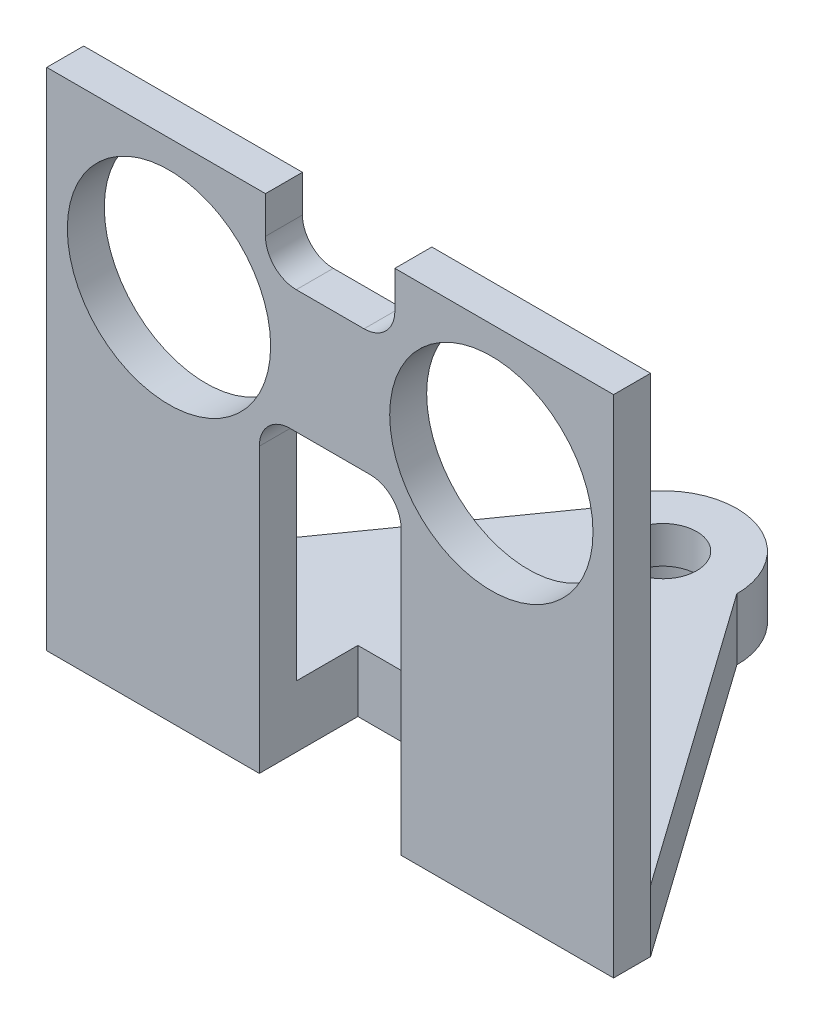
SolidWorks part; units mm, degrees
ref_plane "Front Plane" through (0, 0, 0) normal (0, 0, 1) x (1, 0, 0)
ref_plane "Top Plane" through (0, 0, 0) normal (0, 1, 0) x (1, 0, 0)
ref_plane "Right Plane" through (0, 0, 0) normal (1, 0, 0) x (0, 0, -1)
sketch "Sketch1" plane through (0, 0, 0) normal (0, 0, 1) x (1, 0, 0)
  line L0 (0, 0) -> (0, 10)
  line L1 (2.75, 10) -> (-2.75, 10)
  line L2 (-5.25, 12.5) -> (-5.25, 15.5)
  line L3 (-5.25, 15.5) -> (-23, 15.5)
  line L4 (-23, 15.5) -> (-23, -20.5)
  line L8 (-23, -20.5) -> (-5.75, -20.5)
  line L9 (-5.75, -20.5) -> (-5.75, -2.5)
  line L11 (-3.25, 0) -> (3.25, 0)
  line L12 (5.75, -20.5) -> (5.75, -2.5)
  line L13 (23, -20.5) -> (5.75, -20.5)
  line L14 (23, 15.5) -> (23, -20.5)
  line L15 (5.25, 15.5) -> (23, 15.5)
  line L16 (5.25, 12.5) -> (5.25, 15.5)
  circle A0 centre (-13.08, 5) radius 8.25
  arc A1 (-5.75, -2.5) -> (-3.25, 0) centre (-3.25, -2.5) cw
  arc A2 (-2.75, 10) -> (-5.25, 12.5) centre (-2.75, 12.5) cw
  circle A3 centre (13.08, 5) radius 8.25
  arc A4 (2.75, 10) -> (5.25, 12.5) centre (2.75, 12.5) ccw
  arc A5 (5.75, -2.5) -> (3.25, 0) centre (3.25, -2.5) ccw
  point P3 (0, 5)
  dimension "D8" = 16.5
  dimension "D10" = 2.5
  dimension "D1" = 17.75
  dimension "D2" = 36
  dimension "D3" = 10.5
  dimension "D4" = 5.5
  dimension "D5" = 5
  dimension "D6" = 17.25
  dimension "D7" = 13.08
  dimension "D9" = 5
extrude "Boss-Extrude1" add sketch "Sketch1" along normal blind 3 contours L1 A2 L2 L3 L4 L8 L9 A1 L11 L0 A0 | A5 L12 L13 L14 L15 L16 A4 L1 L0 L11 A3
sketch "Sketch2" plane through (0, -20.5, 0) normal (0, -1, 0) x (1, 0, 0)
  line L0 (-3.25, 3) -> (3.25, 3) construction
  line L1 (-23, 0) -> (-6, -24)
  line L2 (6, -24) -> (23, 0)
  line L3 (0, 0) -> (0, -5.5) construction
  line L4 (-23, 0) -> (-23, 3)
  line L5 (-23, 3) -> (-5.75, 3)
  line L6 (23, 3) -> (23, 0)
  line L7 (-5.75, 3) -> (-5.75, -5)
  line L8 (5.75, 3) -> (5.75, -5)
  line L9 (5.75, -5) -> (-5.75, -5)
  line L10 (5.75, 3) -> (23, 3)
  line L11 (-2.1, -7.6) -> (-3.5, -24)
  line L12 (2.1, -7.6) -> (3.5, -24)
  line L13 (0, -20.5) -> (0, -30) construction
  arc A0 (-6, -24) -> (6, -24) centre (0, -24) ccw
  arc A2 (-3.4494, -23.4068) -> (3.4494, -23.4068) centre (0, -24) ccw
  arc A3 (2.1, -7.6) -> (-2.1, -7.6) centre (0, -7.6) ccw
  point P0 (0, -30)
  point P5 (0, -7.6)
  point P26 (0, -24)
  line M12 (5.75, 0) -> (23, 0)
  line M13 (23, 0) -> (23, 3)
  line M14 (23, 3) -> (5.75, 3)
  line M15 (5.75, 3) -> (5.75, 0)
  dimension "D2" = 6
  dimension "D6" = 7
  dimension "D7" = 2.1
  dimension "D3" = 27
  dimension "D4" = 5
  dimension "D5" = 16.4
extrude "Boss-Extrude2" add sketch "Sketch2" along normal blind 5 contours L1 A0 L2 L8 L9 L7 L5 L4 A3 L12 A2 L11 M12 | M15 M12 M13 M14
sketch "Sketch3" plane through (0, -20.5, 0) normal (0, 1, 0) x (1, 0, 0)
  line L0 (2.1, 7.6) -> (3.4494, 23.4068) construction
  line L1 (-2.1, 7.6) -> (-3.4494, 23.4068) construction
  line L2 (2.1, 7.6) -> (3.4494, 23.4068)
  line L3 (-2.1, 7.6) -> (-3.4494, 23.4068)
  arc A0 (-2.1, 7.6) -> (2.1, 7.6) centre (0, 7.6) ccw construction
  arc A1 (3.4494, 23.4068) -> (-3.4494, 23.4068) centre (0, 24) ccw construction
  arc A2 (-2.1, 7.6) -> (2.1, 7.6) centre (0, 7.6) ccw
  arc A3 (3.4494, 23.4068) -> (-3.4494, 23.4068) centre (0, 24) ccw
extrude "Boss-Extrude3" add sketch "Sketch3" against normal blind 3
sketch "Sketch4" plane through (0, -23.5, 0) normal (0, -1, 0) x (1, 0, 0)
  line L1 (5.75, -5) -> (-5.75, -5) construction
  line L2 (-5.75, 0) -> (-5.75, -5) construction
  circle A0 centre (0, -24) radius 2.75
  circle A1 centre (0, -19.5) radius 0.6
  circle A2 centre (0, -16) radius 0.6
  circle A3 centre (0, -12.5) radius 0.6
  circle A4 centre (0, -9) radius 0.6
  point P0 (0, -24)
  point P4 (0, -19.5)
  point P7 (0, 0)
  point P15 (0, 0)
  dimension "D3" = 1.2
  dimension "D5" = 3.5
  dimension "D8" = 1.2
  dimension "D9" = 1.2
  dimension "D14" = 1.2
  dimension "D13" = 5.5
  dimension "D2" = 4.5
  dimension "D4" = 5.75
  dimension "D6" = 3.5
  dimension "D7" = 3.5
  dimension "D11" = 4
  dimension "D12" = 14.5
extrude "Cut-Extrude1" cut sketch "Sketch4" against normal through all
